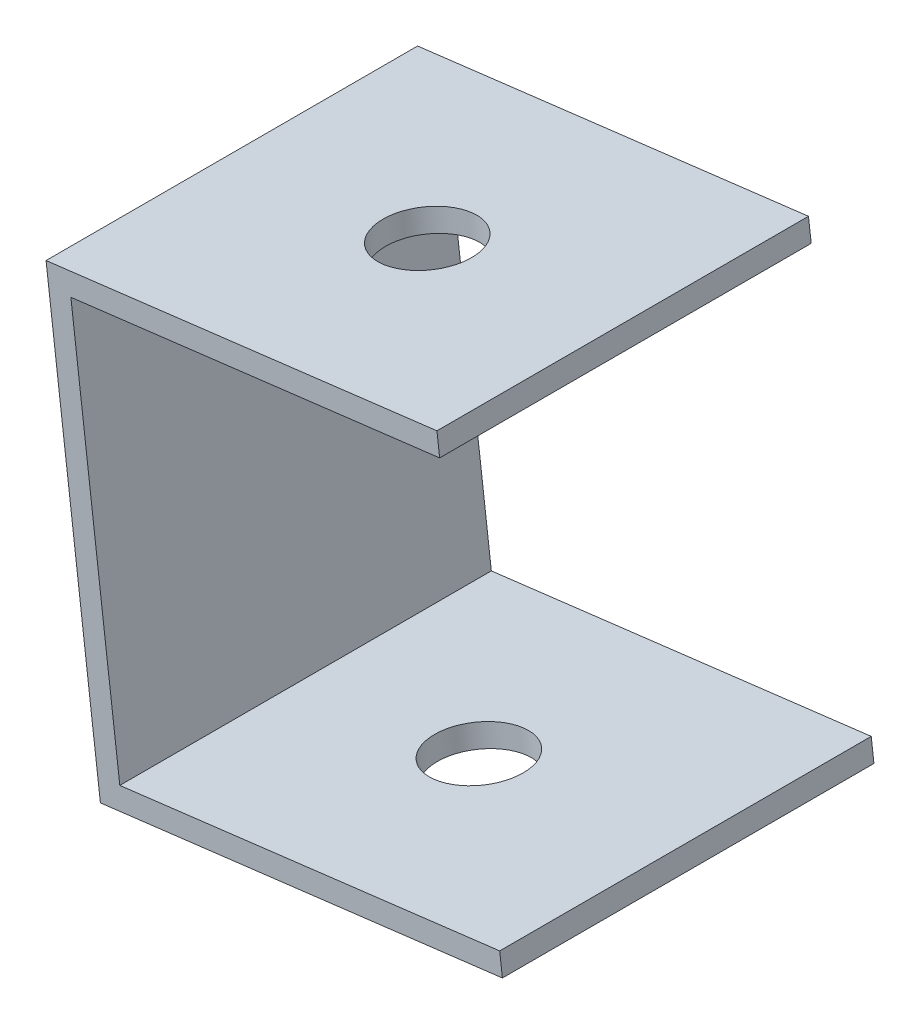
SolidWorks part; units mm, degrees
ref_plane "Front Plane" through (0, 0, 0) normal (0, 0, 1) x (1, 0, 0)
ref_plane "Top Plane" through (0, 0, 0) normal (0, 1, 0) x (1, 0, 0)
ref_plane "Right Plane" through (0, 0, 0) normal (1, 0, 0) x (0, 0, -1)
sketch "Sketch1" plane through (0, 0, 0) normal (0, 0, 1) x (1, 0, 0)
  line L0 (0, 0) -> (-7.3122, 59.5528)
  line L1 (-7.3122, 59.5528) -> (45.2928, 66.0118)
  line L2 (45.2928, 66.0118) -> (45.6584, 63.0342)
  line L3 (45.6584, 63.0342) -> (-3.9689, 56.9407)
  line L4 (-3.9689, 56.9407) -> (2.612, 3.3432)
  line L5 (2.612, 3.3432) -> (53.7366, 9.6206)
  line L6 (53.7366, 9.6206) -> (54.1022, 6.6429)
  line L7 (54.1022, 6.6429) -> (0, 0)
  line L8 (0, 0) -> (-16.5092, 0) construction
  dimension "D1" = 3
  dimension "D2" = 3
  dimension "D3" = 54
  dimension "D4" = 50
  dimension "D5" = 83
extrude "Boss-Extrude1" add sketch "Sketch1" along normal blind 50
sketch "Sketch2" plane through (-7.3122, 59.5528, 0) normal (-0.1219, 0.9925, 0) x (0.9925, 0.1219, 0)
  line L1 (53, 0) -> (0, 0) construction
  line L2 (53, -50) -> (53, 0) construction
  circle A0 centre (26.5, -25) radius 6
  point P2 (0, 0)
  point P5 (26.5, 0)
  point P8 (53, -25)
  dimension "D1" = 12
extrude "Cut-Extrude1" cut sketch "Sketch2" against normal up to surface (60 mm away) up to face at (27.0511, 3.3215, 25)
